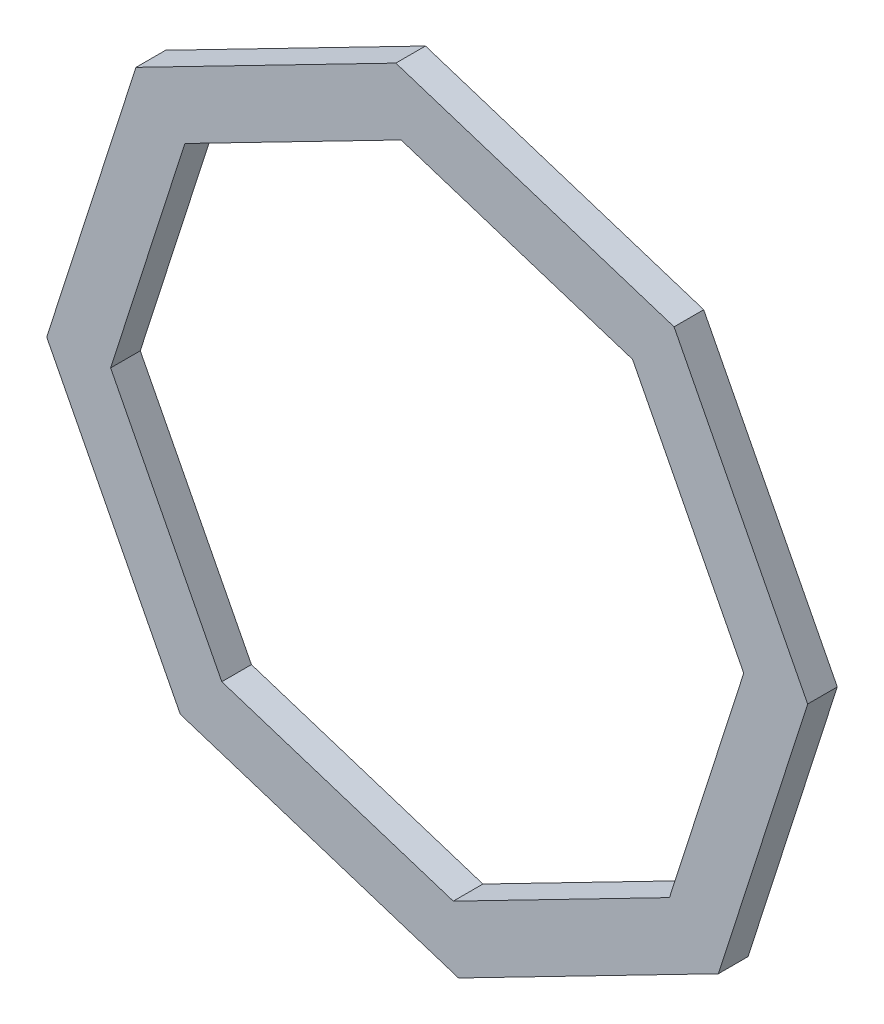
SolidWorks part; units mm, degrees
ref_plane "前视基准面" through (0, 0, 0) normal (0, 0, 1) x (1, 0, 0)
ref_plane "上视基准面" through (0, 0, 0) normal (0, 1, 0) x (1, 0, 0)
ref_plane "右视基准面" through (0, 0, 0) normal (1, 0, 0) x (0, 0, -1)
other "Configuration Table"
sketch "草图1" plane through (0, 0, 0) normal (0, 0, 1) x (1, 0, 0)
  line L0 (34.6602, 40.8857) -> (-4.4021, 53.419)
  line L1 (41.6594, 49.142) -> (-5.291, 64.2063)
  line L2 (-5.291, 64.2063) -> (-49.142, 41.6594)
  line L3 (-49.142, 41.6594) -> (-64.2063, -5.291)
  line L4 (-64.2063, -5.291) -> (-41.6594, -49.142)
  line L5 (-41.6594, -49.142) -> (5.291, -64.2063)
  line L6 (5.291, -64.2063) -> (49.142, -41.6594)
  line L7 (49.142, -41.6594) -> (64.2063, 5.291)
  line L8 (64.2063, 5.291) -> (41.6594, 49.142)
  line L9 (-4.4021, 53.419) -> (-40.8857, 34.6602)
  line L10 (-40.8857, 34.6602) -> (-53.419, -4.4021)
  line L11 (-53.419, -4.4021) -> (-34.6602, -40.8857)
  line L12 (-34.6602, -40.8857) -> (4.4021, -53.419)
  line L13 (4.4021, -53.419) -> (40.8857, -34.6602)
  line L14 (40.8857, -34.6602) -> (53.419, 4.4021)
  line L15 (53.419, 4.4021) -> (34.6602, 40.8857)
  line L24 (64.2063, 5.291) -> (41.6594, 49.142)
  line L25 (41.6594, 49.142) -> (-5.291, 64.2063)
  line L26 (-5.291, 64.2063) -> (-49.142, 41.6594)
  line L27 (-49.142, 41.6594) -> (-64.2063, -5.291)
  line L28 (-64.2063, -5.291) -> (-41.6594, -49.142)
  line L29 (-41.6594, -49.142) -> (5.291, -64.2063)
  line L30 (5.291, -64.2063) -> (49.142, -41.6594)
  line L31 (49.142, -41.6594) -> (64.2063, 5.291)
  line L32 (64.2063, 5.291) -> (41.6594, 49.142) construction
  line L33 (41.6594, 49.142) -> (-5.291, 64.2063) construction
  line L34 (-5.291, 64.2063) -> (-49.142, 41.6594) construction
  line L35 (-49.142, 41.6594) -> (-64.2063, -5.291) construction
  line L36 (-64.2063, -5.291) -> (-41.6594, -49.142) construction
  line L37 (-41.6594, -49.142) -> (5.291, -64.2063) construction
  line L38 (5.291, -64.2063) -> (49.142, -41.6594) construction
  line L39 (49.142, -41.6594) -> (64.2063, 5.291) construction
  circle A0 centre (0, 0) radius 59.52 construction
  dimension "D2" = 10
  dimension "D3" = 0
extrude "凸台-拉伸1" add sketch "草图1" along normal blind 5
